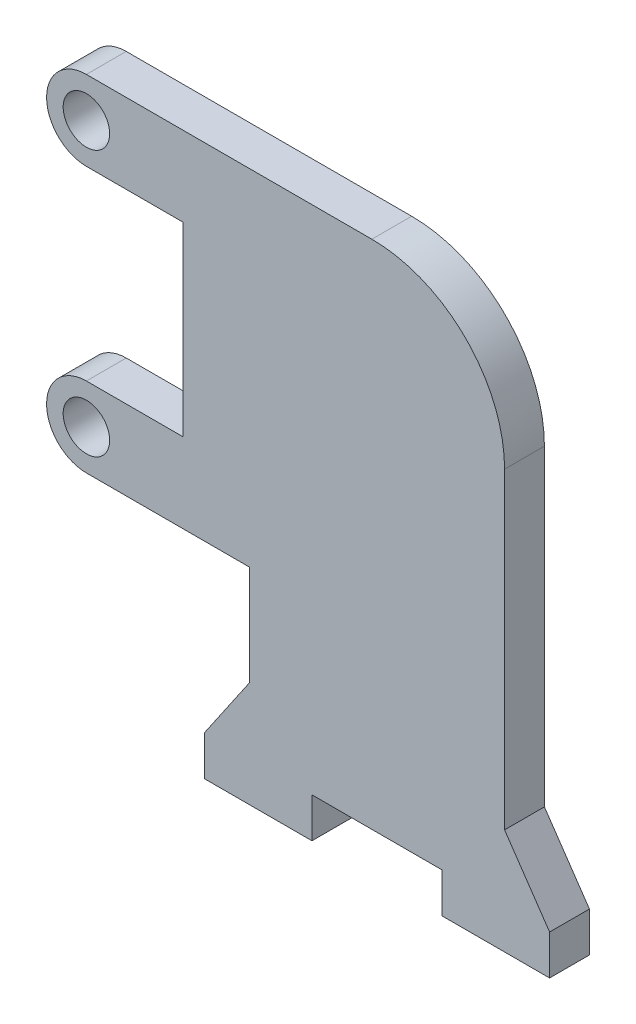
SolidWorks part; units mm, degrees
ref_plane "Front Plane" through (0, 0, 0) normal (0, 0, 1) x (1, 0, 0)
ref_plane "Top Plane" through (0, 0, 0) normal (0, 1, 0) x (1, 0, 0)
ref_plane "Right Plane" through (0, 0, 0) normal (1, 0, 0) x (0, 0, -1)
sketch "Sketch1" plane through (0, 0, 0) normal (0, 0, 1) x (1, 0, 0)
  line L0 (0, 68.4393) -> (0, 9.968) construction
  line L1 (0, 43.5) -> (0, 9.968)
  line L2 (0, 43.5) -> (-31.5, 43.5)
  line L3 (-24.2075, 37.5) -> (-31.5, 37.5)
  line L5 (-24.2075, 23.5) -> (-31.5, 23.5)
  line L6 (-31.5, 17.5) -> (-19.2101, 17.5)
  line L7 (-19.2101, 17.5) -> (-19.2101, 9.968)
  line L8 (-14.5101, 5) -> (-4.7101, 5)
  line L9 (-24.2075, 37.5) -> (-24.2075, 23.5)
  line L10 (-14.5101, 5) -> (-4.7101, 5) construction
  line L12 (-22.6101, 5) -> (-22.6101, 2)
  line L13 (-22.6101, 2) -> (-14.5101, 2)
  line L14 (-14.5101, 5) -> (-14.5101, 2)
  line L15 (-9.6101, 5) -> (-9.6101, 20.5) construction
  line L16 (3.3899, 5) -> (3.3899, 2)
  line L17 (3.3899, 2) -> (-4.7101, 2)
  line L18 (-4.7101, 5) -> (-4.7101, 2)
  line L19 (-22.6101, 5) -> (-19.2101, 9.968)
  line L20 (3.3899, 5) -> (0, 9.968)
  line L26 (0, -3) -> (0, -65.0482) construction
  arc A0 (-31.5, 43.5) -> (-31.5, 37.5) centre (-31.5, 40.5) ccw
  arc A1 (-31.5, 23.5) -> (-31.5, 17.5) centre (-31.5, 20.5) ccw
  circle A2 centre (-31.5, 40.5) radius 1.75
  circle A3 centre (-31.5, 20.5) radius 1.75
  point P8 (-24.2075, 30.5)
  point P13 (-20.71, 30.5)
  dimension "D3" = 3
  dimension "D4" = 3
  dimension "D10" = 3.5
  dimension "D11" = 3.5
  dimension "D1" = 20
  dimension "D2" = 26
  dimension "D5" = 31.5
  dimension "D8" = 8.1
  dimension "D12" = 3
  dimension "D9" = 3
  dimension "D13" = 8.1
extrude "Boss-Extrude1" add sketch "Sketch1" along normal blind 3
fillet "Fillet1" radius 10 1 edges at (0, 43.5, 1.5)
